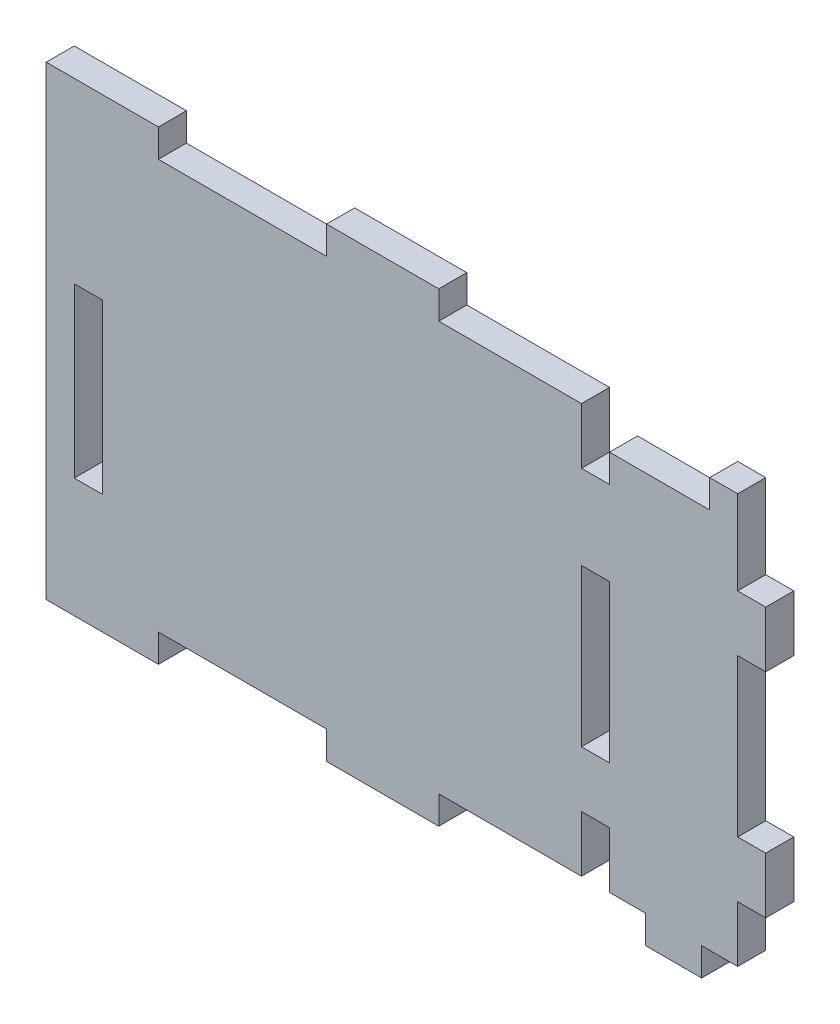
SolidWorks part; units mm, degrees
ref_plane "Plan de face" through (0, 0, 0) normal (0, 0, 1) x (1, 0, 0)
ref_plane "Plan de dessus" through (0, 0, 0) normal (0, 1, 0) x (1, 0, 0)
ref_plane "Plan de droite" through (0, 0, 0) normal (1, 0, 0) x (0, 0, -1)
sketch "Esquisse1" plane through (0, 0, 0) normal (0, 0, 1) x (1, 0, 0)
  line L0 (-271.2689, 30.4361) -> (-271.2689, -42.5639)
  line L1 (-271.2689, -42.5639) -> (-142.9571, -42.5639)
  line L2 (-142.9571, -42.5639) -> (-142.9571, 30.4361)
  line L3 (-142.9571, 30.4361) -> (-271.2689, 30.4361)
  dimension "D1" = 73
extrude "Boss.-Extru.1" add sketch "Esquisse1" along normal blind 5
sketch "Esquisse3" plane through (0, 0, 0) normal (0, 0, -1) x (-1, 0, 0)
  line L0 (142.9571, 30.4361) -> (271.2689, 30.4361) construction
  line L1 (175.8171, 20.4361) -> (170.8171, 20.4361)
  line L2 (175.8171, 20.4361) -> (175.8171, 30.4361)
  line L3 (175.8171, 30.4361) -> (170.8171, 30.4361)
  line L4 (170.8171, 20.4361) -> (170.8171, 30.4361)
  line L5 (271.2689, -42.5639) -> (142.9571, -42.5639) construction
  line L6 (175.8171, 5.4361) -> (170.8171, 5.4361)
  line L7 (175.8171, 5.4361) -> (175.8171, -22.5639)
  line L8 (175.8171, -22.5639) -> (170.8171, -22.5639)
  line L9 (170.8171, 5.4361) -> (170.8171, -22.5639)
  line L10 (175.8171, -32.5639) -> (170.8171, -32.5639)
  line L11 (175.8171, -32.5639) -> (175.8171, -42.5639)
  line L12 (175.8171, -42.5639) -> (170.8171, -42.5639)
  line L13 (170.8171, -32.5639) -> (170.8171, -42.5639)
  line L15 (142.9571, 30.4361) -> (147.9571, 30.4361)
  line L16 (142.9571, 30.4361) -> (142.9571, 15.4361)
  line L17 (142.9571, 15.4361) -> (147.9571, 15.4361)
  line L18 (147.9571, 30.4361) -> (147.9571, 15.4361)
  line L20 (147.9571, 5.4361) -> (142.9571, 5.4361)
  line L21 (147.9571, 5.4361) -> (147.9571, -22.5639)
  line L22 (147.9571, -22.5639) -> (142.9571, -22.5639)
  line L23 (142.9571, 5.4361) -> (142.9571, -22.5639)
  line L25 (147.9571, -32.5639) -> (142.9571, -32.5639)
  line L26 (147.9571, -32.5639) -> (147.9571, -42.5639)
  line L27 (147.9571, -42.5639) -> (142.9571, -42.5639)
  line L28 (142.9571, -32.5639) -> (142.9571, -42.5639)
  line L29 (266.2689, 3.7111) -> (261.2689, 3.7111)
  line L30 (266.2689, 3.7111) -> (266.2689, -26.2889)
  line L31 (266.2689, -26.2889) -> (261.2689, -26.2889)
  line L32 (261.2689, 3.7111) -> (261.2689, -26.2889)
  dimension "D1" = 15
  dimension "D2" = 5
  dimension "D3" = 10
  dimension "D4" = 5
extrude "Enlèv. mat.-Extru.1" cut sketch "Esquisse3" against normal blind 5
sketch "Esquisse4" plane through (0, 0, 5) normal (0, 0, 1) x (1, 0, 0)
  line L1 (-170.8171, 30.4361) -> (-152.9571, 30.4361)
  line L2 (-170.8171, 30.4361) -> (-170.8171, 25.4361)
  line L3 (-170.8171, 25.4361) -> (-152.9571, 25.4361)
  line L4 (-152.9571, 30.4361) -> (-152.9571, 25.4361)
extrude "Enlèv. mat.-Extru.2" cut sketch "Esquisse4" against normal blind 5
sketch "Esquisse5" plane through (0, 0, 0) normal (0, 0, -1) x (-1, 0, 0)
  line L0 (175.8171, 30.4361) -> (271.2689, 30.4361) construction
  line L1 (201.2689, 30.4361) -> (221.2689, 30.4361)
  line L2 (201.2689, 30.4361) -> (201.2689, 35.4361)
  line L3 (201.2689, 35.4361) -> (221.2689, 35.4361)
  line L4 (221.2689, 30.4361) -> (221.2689, 35.4361)
  line L5 (271.2689, -6.0639) -> (235.3282, -6.0639) construction
  line L6 (271.2689, 30.4361) -> (251.2689, 30.4361)
  line L7 (271.2689, 30.4361) -> (271.2689, 35.4361)
  line L8 (271.2689, 35.4361) -> (251.2689, 35.4361)
  line L9 (251.2689, 30.4361) -> (251.2689, 35.4361)
  line L10 (271.2689, 30.4361) -> (271.2689, -42.5639) construction
  line L11 (251.2689, -42.5639) -> (251.2689, -47.5639)
  line L12 (271.2689, -47.5639) -> (251.2689, -47.5639)
  line L13 (271.2689, -42.5639) -> (271.2689, -47.5639)
  line L14 (271.2689, -42.5639) -> (251.2689, -42.5639)
  line L15 (221.2689, -42.5639) -> (221.2689, -47.5639)
  line L16 (201.2689, -47.5639) -> (221.2689, -47.5639)
  line L17 (201.2689, -42.5639) -> (201.2689, -47.5639)
  line L18 (201.2689, -42.5639) -> (221.2689, -42.5639)
  line L19 (170.8171, -42.5639) -> (147.9571, -42.5639) construction
  line L20 (154.3871, -42.5639) -> (164.3871, -42.5639)
  line L21 (154.3871, -42.5639) -> (154.3871, -47.5639)
  line L22 (154.3871, -47.5639) -> (164.3871, -47.5639)
  line L23 (164.3871, -42.5639) -> (164.3871, -47.5639)
  line L24 (147.9571, -42.5639) -> (147.9571, -32.5639) construction
  dimension "D1" = 5
  dimension "D2" = 20
  dimension "D3" = 20
  dimension "D4" = 30
  dimension "D5" = 5
  dimension "D6" = 6.43
  dimension "D7" = 10
extrude "Boss.-Extru.2" add sketch "Esquisse5" against normal blind 5
